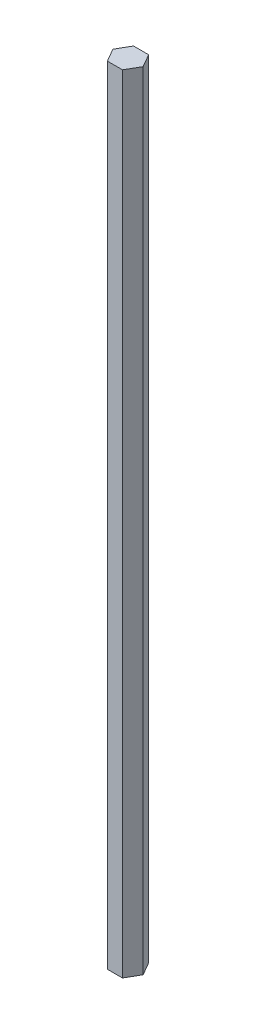
SolidWorks part; units mm, degrees
ref_plane "前视基准面" through (0, 0, 0) normal (0, 0, 1) x (1, 0, 0)
ref_plane "上视基准面" through (0, 0, 0) normal (0, 1, 0) x (1, 0, 0)
ref_plane "右视基准面" through (0, 0, 0) normal (1, 0, 0) x (0, 0, -1)
sketch "草图1" plane through (0, 0, 0) normal (0, 1, 0) x (1, 0, 0)
  line L1 (4.8, 0) -> (2.4, 4.1569)
  line L2 (2.4, 4.1569) -> (-2.4, 4.1569)
  line L3 (-2.4, 4.1569) -> (-4.8, 0)
  line L4 (-4.8, 0) -> (-2.4, -4.1569)
  line L5 (-2.4, -4.1569) -> (2.4, -4.1569)
  line L6 (2.4, -4.1569) -> (4.8, 0)
  circle A0 centre (0, 0) radius 4.1569 construction
  dimension "D1" = 9.6
extrude "凸台-拉伸1" add sketch "草图1" along normal blind 250
